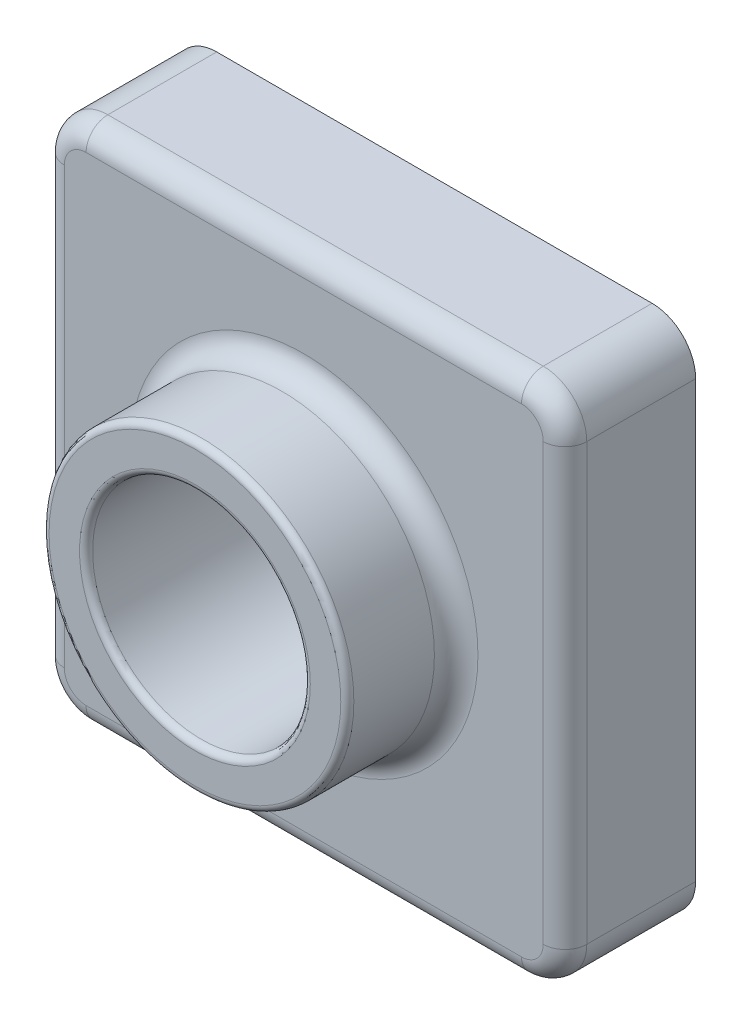
SolidWorks part; units mm, degrees
material "Chrome Stainless Steel"
ref_plane "Front Plane" through (0, 0, 0) normal (0, 0, 1) x (1, 0, 0)
ref_plane "Top Plane" through (0, 0, 0) normal (0, 1, 0) x (1, 0, 0)
ref_plane "Right Plane" through (0, 0, 0) normal (1, 0, 0) x (0, 0, -1)
sketch "Sketch1" plane through (0, 0, 0) normal (0, 0, 1) x (1, 0, 0)
  line L1 (0, 0) -> (120, 0)
  line L2 (0, 0) -> (0, 120)
  line L3 (0, 120) -> (120, 120)
  line L4 (120, 0) -> (120, 120)
  dimension "D1" = 120
  dimension "D2" = 120
extrude "Boss-Extrude1" add sketch "Sketch1" along normal blind 30
sketch "Sketch2" plane through (0, 0, 30) normal (0, 0, 1) x (1, 0, 0)
  line L0 (120, 120) -> (0, 120) construction
  line L1 (120, 0) -> (120, 120) construction
  circle A0 centre (60, 60) radius 35
  dimension "D1" = 70
  dimension "D2" = 60
  dimension "D3" = 60
extrude "Boss-Extrude2" add sketch "Sketch2" along normal blind 25
sketch "Sketch3" plane through (0, 0, 55) normal (0, 0, 1) x (1, 0, 0)
  circle A0 centre (60, 60) radius 25
  dimension "D1" = 50
extrude "Cut-Extrude1" cut sketch "Sketch3" against normal through all
fillet "Fillet1" radius 10 4 edges at (0, 0, 15) (0, 120, 15) (120, 120, 15) (120, 0, 15)
fillet "Fillet2" radius 1.5 2 edges at (95, 60, 55) (85, 60, 55)
fillet "Fillet3" radius 5 9 edges at (2.9289, 117.0711, 30) (60, 120, 30) (117.0711, 117.0711, 30) (120, 60, 30) (117.0711, 2.9289, 30) (60, 0, 30) (2.9289, 2.9289, 30) (0, 60, 30) (95, 60, 30)
shell "Shell1" thickness 2
